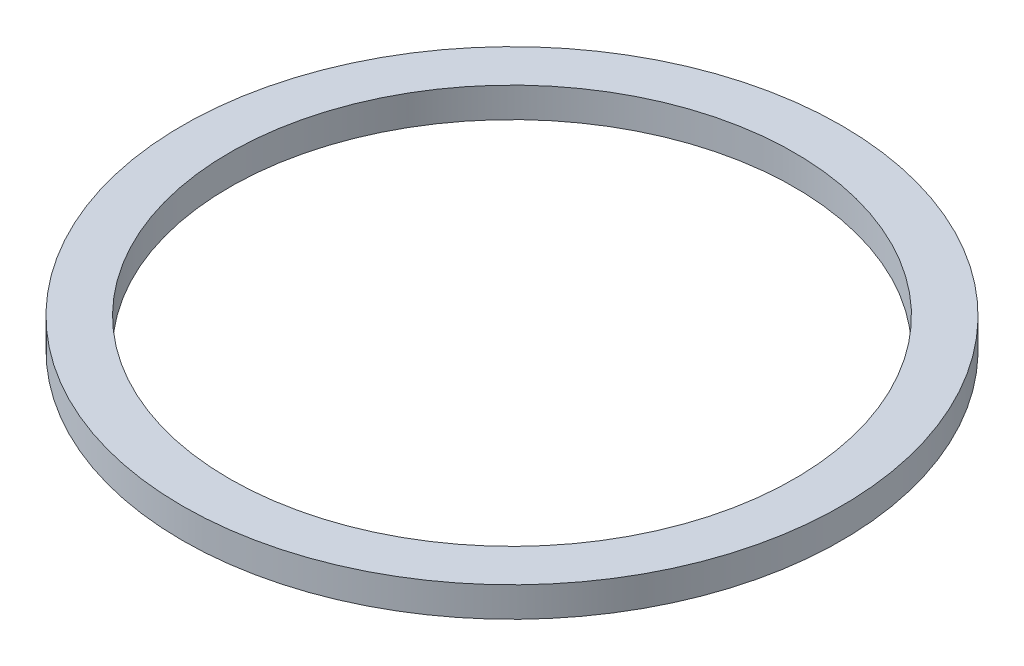
SolidWorks part; units mm, degrees
ref_plane "Front Plane" through (0, 0, 0) normal (0, 0, 1) x (1, 0, 0)
ref_plane "Top Plane" through (0, 0, 0) normal (0, 1, 0) x (1, 0, 0)
ref_plane "Right Plane" through (0, 0, 0) normal (1, 0, 0) x (0, 0, -1)
sketch "Sketch1" plane through (0, 0, 0) normal (0, 1, 0) x (1, 0, 0)
  circle A0 centre (0, 0) radius 17.5
  circle A1 centre (0, 0) radius 15
  dimension "D1" = 35
  dimension "D2" = 30
extrude "Boss-Extrude1" add sketch "Sketch1" along normal blind 1.5875
